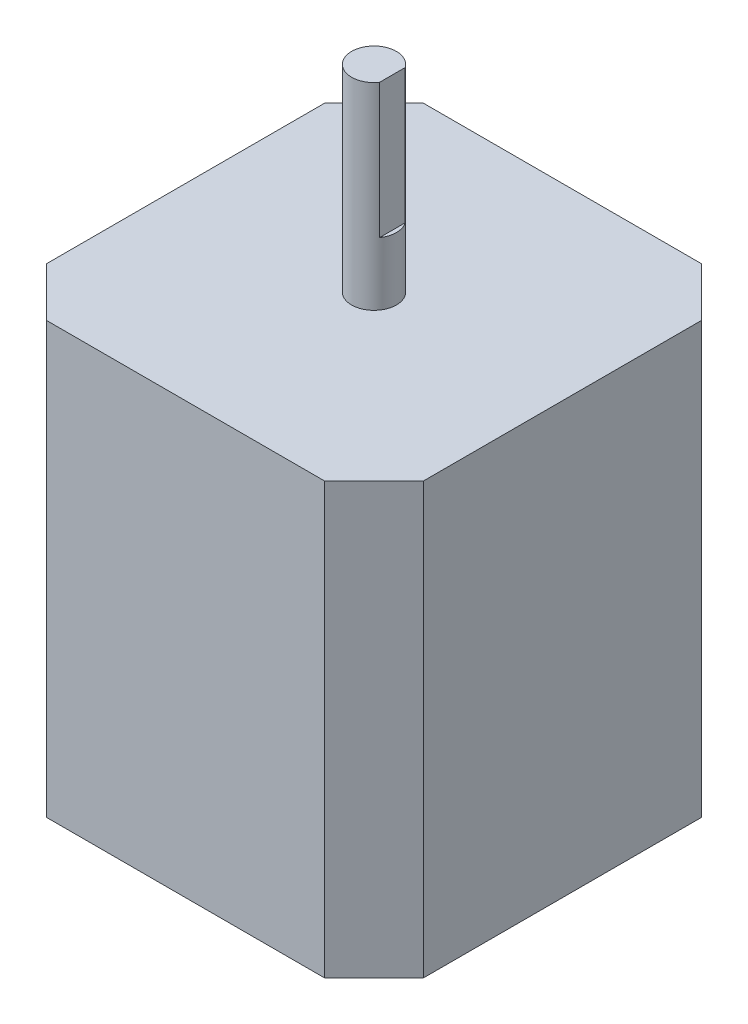
SolidWorks part; units mm, degrees
ref_plane "Front Plane" through (0, 0, 0) normal (0, 0, 1) x (1, 0, 0)
ref_plane "Top Plane" through (0, 0, 0) normal (0, 1, 0) x (1, 0, 0)
ref_plane "Right Plane" through (0, 0, 0) normal (1, 0, 0) x (0, 0, -1)
sketch "Sketch1" plane through (0, 0, 0) normal (0, 1, 0) x (1, 0, 0)
  line L1 (0, 0) -> (42, 0)
  line L2 (0, 0) -> (0, 42)
  line L3 (0, 42) -> (42, 42)
  line L4 (42, 0) -> (42, 42)
  dimension "D1" = 42
  dimension "D2" = 42
extrude "Body" add sketch "Sketch1" along normal blind 48
chamfer "Chamfer1" distance 5.5 angle 45 4 edges at (0, 24, 0) (0, 24, -42) (42, 24, -42) (42, 24, 0)
sketch "Sketch2" plane through (0, 48, 0) normal (0, 1, 0) x (1, 0, 0)
  line L3 (42, 5.5) -> (42, 36.5) construction
  line L4 (5.5, 0) -> (36.5, 0) construction
  circle A0 centre (21, 21) radius 2.5
  point P2 (18.8001, 21.0303)
  point P5 (42, 21)
  point P6 (42, 21)
  point P7 (19.6338, 21)
  point P12 (21, 0)
  dimension "D1" = 5
extrude "Shaft" add sketch "Sketch2" along normal blind 22
sketch "Sketch3" plane through (0, 70, 0) normal (0, 1, 0) x (1, 0, 0)
  line L0 (23.05, 19.5691) -> (23.05, 22.4309)
  arc A0 (23.05, 19.5691) -> (23.05, 22.4309) centre (21, 21) cw
  circle A1 centre (21, 21) radius 2.5 construction
  circle A2 centre (21, 21) radius 2.5
  point P8 (18.5, 21)
  circle M1 centre (21, 21) radius 2.5
  dimension "D1" = 4.55
extrude "ShaftOrienter" cut sketch "Sketch3" against normal blind 15 contours L0 M1 | A2
